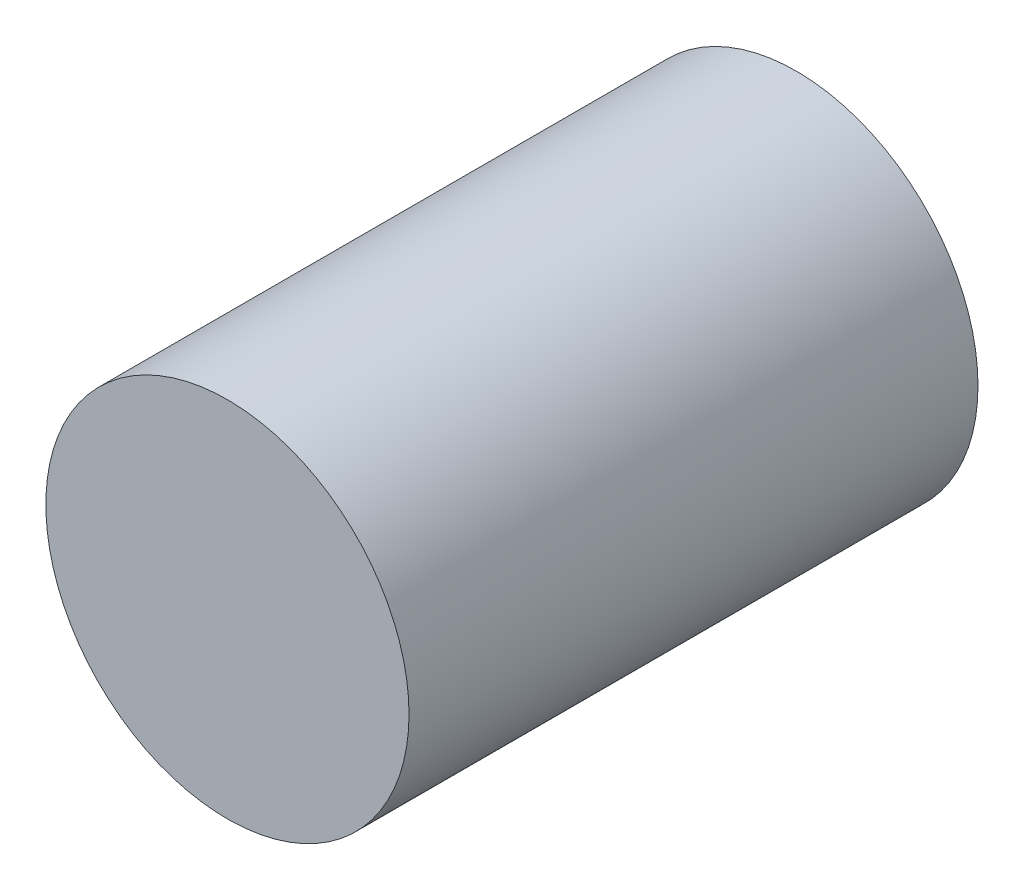
SolidWorks part; units mm, degrees
ref_plane "Front Plane" through (0, 0, 0) normal (0, 0, 1) x (1, 0, 0)
ref_plane "Top Plane" through (0, 0, 0) normal (0, 1, 0) x (1, 0, 0)
ref_plane "Right Plane" through (0, 0, 0) normal (1, 0, 0) x (0, 0, -1)
sketch "Sketch1" plane through (0, 0, 0) normal (0, 0, 1) x (1, 0, 0)
  circle A0 centre (0, 0) radius 15
  dimension "D1" = 30
extrude "Boss-Extrude1" add sketch "Sketch1" along normal mid plane 47
sketch "Sketch2" plane through (0, 0, -23.5) normal (0, 0, -1) x (-1, 0, 0)
  circle A0 centre (-8, 8) radius 1.65
  circle A1 centre (8, 8) radius 1.65
  circle A2 centre (8, -8) radius 1.65
  circle A3 centre (-8, -8) radius 1.65
  point P2 (0, 0)
  point P4 (-9.15, -8.6627)
  point P5 (0, 0)
  point P12 (0, 0)
  dimension "D1" = 3.3
  dimension "D2" = 8
  dimension "D3" = 8
  dimension "D4" = 4
extrude "Cut-Extrude1" cut sketch "Sketch2" against normal blind 10 contours A1 | A2 | A3 | A0
